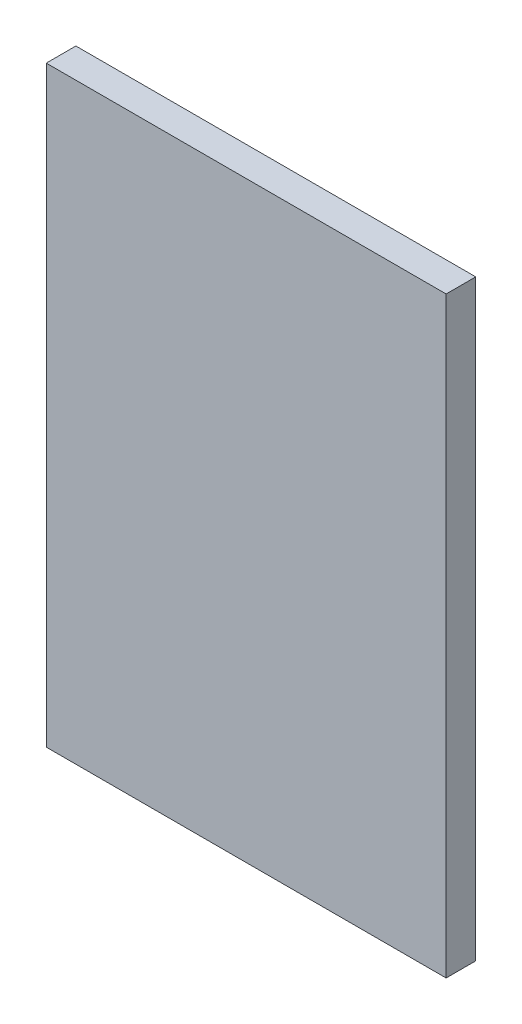
SolidWorks part; units mm, degrees
ref_plane "Alzado" through (0, 0, 0) normal (0, 0, 1) x (1, 0, 0)
ref_plane "Planta" through (0, 0, 0) normal (0, 1, 0) x (1, 0, 0)
ref_plane "Vista lateral" through (0, 0, 0) normal (1, 0, 0) x (0, 0, -1)
ref_plane "Plano_CajaSujetadoraSur" through (0, 630, 0) normal (0, 1, 0) x (1, 0, 0)
sketch "SkCajaSujetadoraSur" plane through (0, 630, 0) normal (0, 1, 0) x (1, 0, 0)
  line L1 (-135, 135) -> (135, 135)
  line L2 (-135, 135) -> (-135, 155)
  line L3 (-135, 155) -> (135, 155)
  line L4 (135, 135) -> (135, 155)
extrude "CajaSujetadoraSur" add sketch "SkCajaSujetadoraSur" along normal blind 400 separate body
